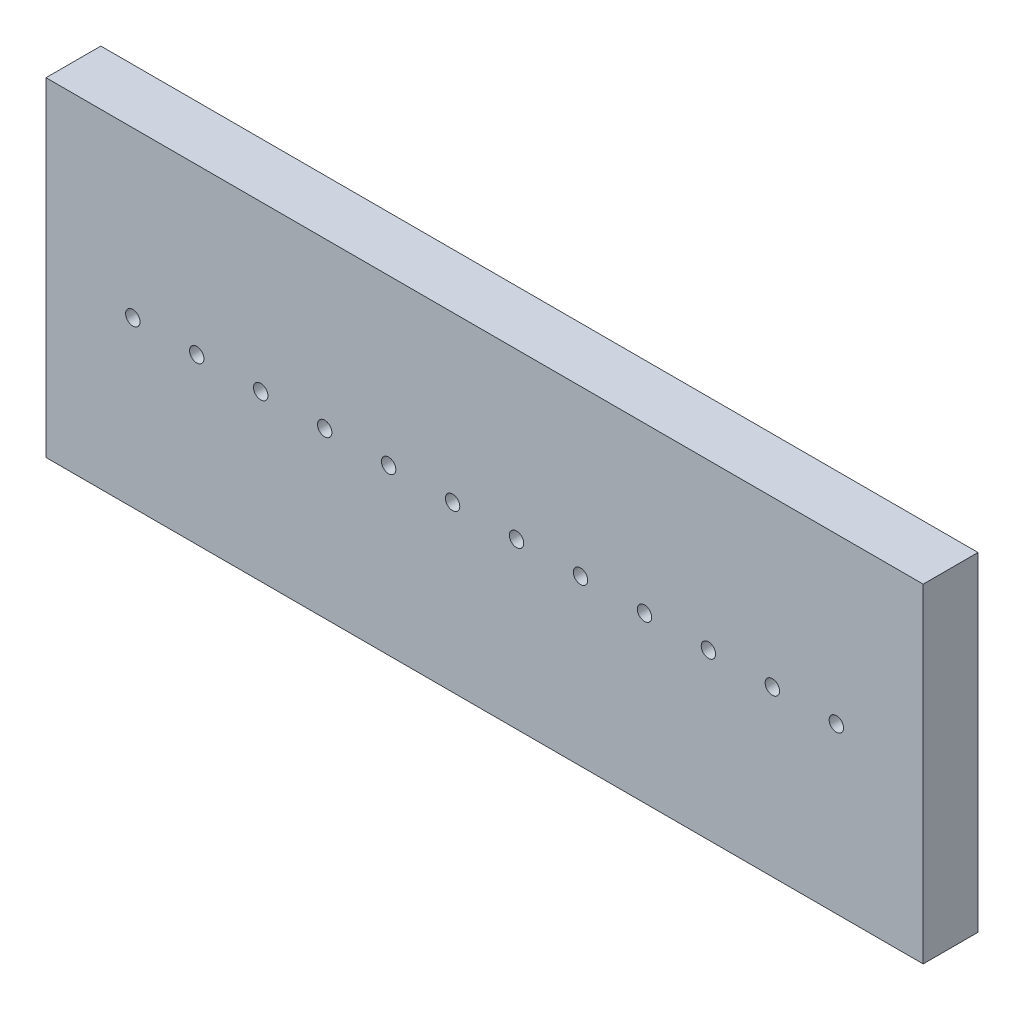
SolidWorks part; units mm, degrees
ref_plane "Plan de face" through (0, 0, 0) normal (0, 0, 1) x (1, 0, 0)
ref_plane "Plan de dessus" through (0, 0, 0) normal (0, 1, 0) x (1, 0, 0)
ref_plane "Plan de droite" through (0, 0, 0) normal (1, 0, 0) x (0, 0, -1)
sketch "Esquisse1" plane through (0, 0, 0) normal (0, 0, 1) x (1, 0, 0)
  line L1 (-101.6, -38.1) -> (101.6, -38.1)
  line L2 (-101.6, -38.1) -> (-101.6, 38.1)
  line L3 (-101.6, 38.1) -> (101.6, 38.1)
  line L4 (101.6, -38.1) -> (101.6, 38.1)
  line L5 (-101.6, -38.1) -> (101.6, 38.1) construction
  line L6 (-101.6, 38.1) -> (101.6, -38.1) construction
  point P0 (0, 0)
  dimension "D1" = 203.2
  dimension "D2" = 76.2
extrude "Boss.-Extru.1" add sketch "Esquisse1" along normal blind 12.7
sketch "Esquisse2" plane through (0, 0, 0) normal (0, 0, -1) x (-1, 0, 0)
  line L0 (101.6, 38.1) -> (88.9, 38.1) construction
  line L1 (-101.6, 38.1) -> (101.6, 38.1) construction
  line L2 (88.9, 38.1) -> (88.9, -38.1) construction
  line L3 (101.6, -38.1) -> (-101.6, -38.1) construction
  line L4 (88.9, 0) -> (81.4921, 0) construction
  line L5 (81.4921, 0) -> (66.6763, 0) construction
  line L6 (74.0842, 38.1) -> (74.0842, -38.1) construction
  line L7 (-101.6, 38.1) -> (-88.9, 38.1) construction
  line L8 (-88.9, 38.1) -> (-88.9, -38.1) construction
  line L9 (-88.9, -38.1) -> (-88.9, 0) construction
  line L10 (-88.9, 0) -> (-81.4819, 0) construction
  line L11 (66.6763, 0) -> (51.8605, 0) construction
  line L12 (51.8605, 0) -> (37.0446, 0) construction
  line L13 (37.0446, 0) -> (22.2288, 0) construction
  line L14 (22.2288, 0) -> (7.413, 0) construction
  line L15 (7.413, 0) -> (-7.4028, 0) construction
  line L16 (-7.4028, 0) -> (-22.2186, 0) construction
  line L17 (-22.2186, 0) -> (-37.0345, 0) construction
  line L18 (-37.0345, 0) -> (-51.8503, 0) construction
  line L19 (-51.8503, 0) -> (-66.6661, 0) construction
  line L20 (-66.6661, 0) -> (-81.4819, 0) construction
  line L21 (-81.4819, 0) -> (-88.9, 0) construction
  line L22 (-88.9, 38.1) -> (88.9, 38.1) construction
  circle A0 centre (81.4921, 0) radius 1.6669
  circle A1 centre (66.6763, 0) radius 1.6669
  circle A2 centre (51.8605, 0) radius 1.6669
  circle A3 centre (37.0446, 0) radius 1.6669
  circle A4 centre (22.2288, 0) radius 1.6669
  circle A5 centre (7.413, 0) radius 1.6669
  circle A6 centre (-7.4028, 0) radius 1.6669
  circle A7 centre (-22.2186, 0) radius 1.6669
  circle A8 centre (-37.0345, 0) radius 1.6669
  circle A9 centre (-51.8503, 0) radius 1.6669
  circle A10 centre (-66.6661, 0) radius 1.6669
  circle A11 centre (-81.4819, 0) radius 1.6669
  dimension "D1" = 12
  dimension "D2" = 14.8158
extrude "Enlèv. mat.-Extru.1" cut sketch "Esquisse2" against normal through all
